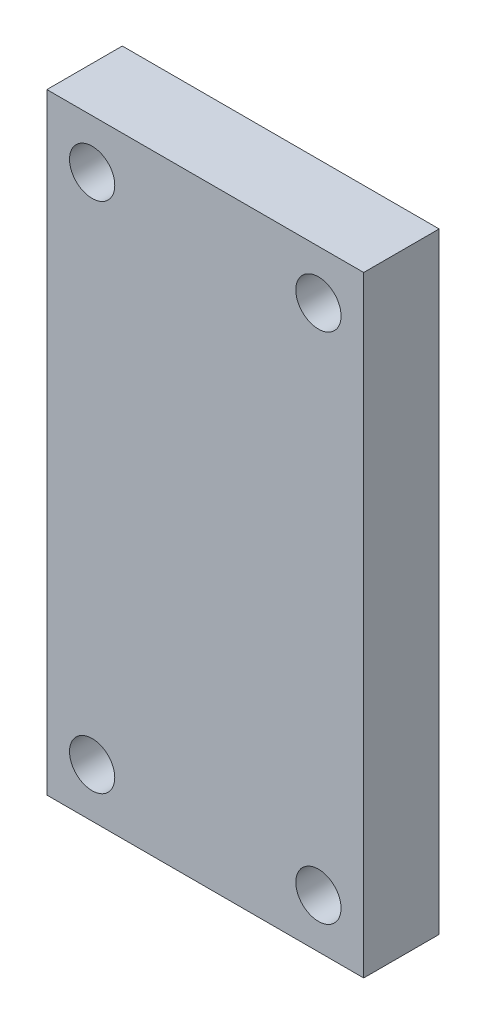
SolidWorks part; units mm, degrees
ref_plane "Ebene vorne" through (0, 0, 0) normal (0, 0, 1) x (1, 0, 0)
ref_plane "Ebene oben" through (0, 0, 0) normal (0, 1, 0) x (1, 0, 0)
ref_plane "Ebene rechts" through (0, 0, 0) normal (1, 0, 0) x (0, 0, -1)
sketch "Skizze1" plane through (0, 0, 0) normal (0, 0, 1) x (1, 0, 0)
  line L1 (-10.5, 20.25) -> (10.5, 20.25)
  line L2 (-10.5, 20.25) -> (-10.5, -20.25)
  line L3 (-10.5, -20.25) -> (10.5, -20.25)
  line L4 (10.5, 20.25) -> (10.5, -20.25)
  line L5 (-10.5, 20.25) -> (10.5, -20.25) construction
  line L6 (-10.5, -20.25) -> (10.5, 20.25) construction
  point P0 (0, 0)
  dimension "D1" = 40.5
  dimension "D2" = 21
extrude "Aufsatz-Linear austragen1" add sketch "Skizze1" along normal blind 5
sketch "Skizze2" plane through (0, 0, 5) normal (0, 0, 1) x (1, 0, 0)
  line L1 (7.5, -17) -> (-7.5, -17) construction
  line L2 (7.5, -17) -> (7.5, 17) construction
  line L3 (7.5, 17) -> (-7.5, 17) construction
  line L4 (-7.5, -17) -> (-7.5, 17) construction
  line L5 (7.5, -17) -> (-7.5, 17) construction
  line L6 (7.5, 17) -> (-7.5, -17) construction
  circle A0 centre (-7.5, 17) radius 1.5
  circle A1 centre (7.5, 17) radius 1.5
  circle A2 centre (-7.5, -17) radius 1.5
  circle A3 centre (7.5, -17) radius 1.5
  point P0 (0, 0)
  dimension "D1" = 3
  dimension "D2" = 15
  dimension "D3" = 34
extrude "Schnitt-Linear austragen1" cut sketch "Skizze2" against normal through all
